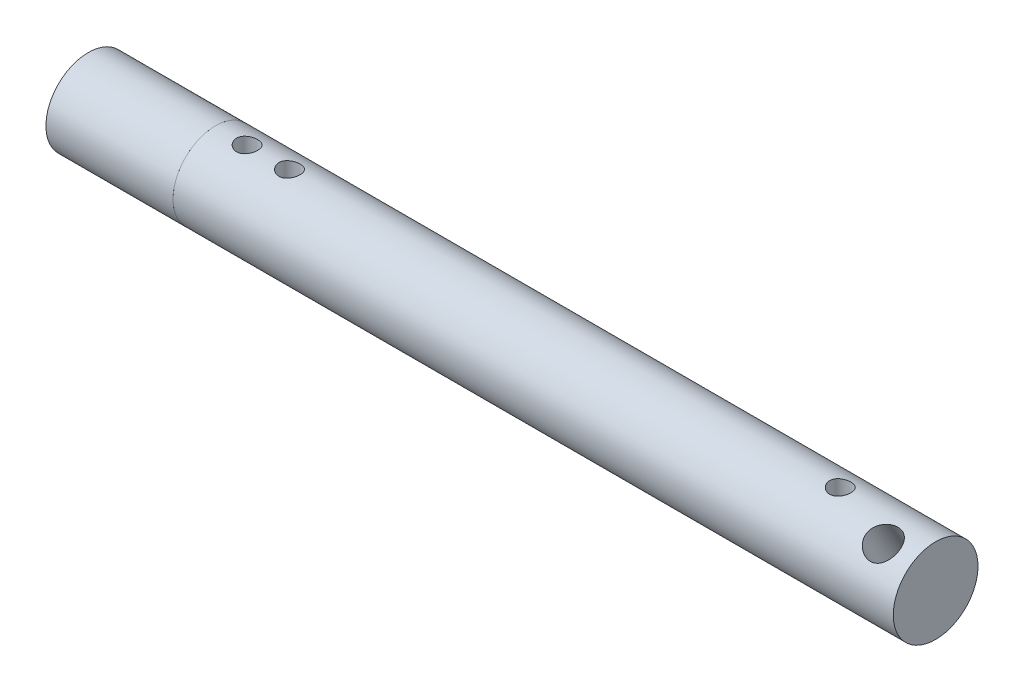
SolidWorks part; units mm, degrees
ref_plane "Front Plane" through (0, 0, 0) normal (0, 0, 1) x (1, 0, 0)
ref_plane "Top Plane" through (0, 0, 0) normal (0, 1, 0) x (1, 0, 0)
ref_plane "Right Plane" through (0, 0, 0) normal (1, 0, 0) x (0, 0, -1)
sketch "Sketch1" plane through (0, 0, 0) normal (1, 0, 0) x (0, 0, -1)
  line L0 (0, 0) -> (0, 12.7)
  line L1 (12.7, 3.403) -> (9.297, 9.297)
  line L2 (9.297, 9.297) -> (3.403, 12.7)
  line L3 (3.403, 12.7) -> (-3.403, 12.7)
  line L4 (-3.403, 12.7) -> (-9.297, 9.297)
  line L5 (-9.297, 9.297) -> (-12.7, 3.403)
  line L6 (-12.7, 3.403) -> (-12.7, -3.403)
  line L7 (-12.7, -3.403) -> (-9.297, -9.297)
  line L8 (-9.297, -9.297) -> (-3.403, -12.7)
  line L9 (-3.403, -12.7) -> (3.403, -12.7)
  line L10 (3.403, -12.7) -> (9.297, -9.297)
  line L11 (9.297, -9.297) -> (12.7, -3.403)
  line L12 (12.7, -3.403) -> (12.7, 3.403)
  line L13 (0, 0) -> (6.35, 10.9985)
  circle A0 centre (0, 0) radius 12.7
  circle A1 centre (0, 0) radius 12.7 construction
extrude "Boss-Extrude1" add sketch "Sketch1" along normal blind 215.9 contours L3 L4 L5 L6 L7 L8 L9 L10 L11 L12 L1 L2
sketch "Sketch2" plane through (0, 12.7, 0) normal (0, 1, 0) x (1, 0, 0)
  line L0 (0, 0) -> (9.525, 0)
  line L1 (0, 0) -> (22.225, 0)
  line L2 (0, 0) -> (187.325, 0)
  circle A0 centre (9.525, 0) radius 3.175
  circle A1 centre (22.225, 0) radius 3.175
  circle A2 centre (187.325, 0) radius 3.175
sketch "Sketch3" plane through (0, 10.9985, 6.35) normal (0, 0.866, 0.5) x (1, 0, 0)
  line L0 (0, 0) -> (206.375, 0)
  circle A0 centre (206.375, 0) radius 4.7625
extrude "Cut-Extrude1" cut sketch "Sketch2" against normal blind 215.9 contours L2 A1 L1 | L1 A1 L2 | L2 A0 L1 | L1 A0 L2 | A2
extrude "Cut-Extrude2" cut sketch "Sketch3" against normal blind 215.9 contours A0
sketch "Sketch4" plane through (0, 0, 0) normal (-1, 0, 0) x (0, 0, 1)
  circle A0 centre (0, 0) radius 12.7
  circle A1 centre (0, 0) radius 25.4351
extrude "Cut-Extrude6" cut sketch "Sketch4" against normal blind 222.25
sketch "Sketch5" plane through (0, 0, 0) normal (-1, 0, 0) x (0, 0, 1)
  circle A0 centre (0, 0) radius 12.7
extrude "Boss-Extrude2" add sketch "Sketch5" along normal blind 38.1 separate body
sketch "Sketch6" plane through (-38.1, 0, 0) normal (-1, 0, 0) x (0, 0, 1)
  circle A0 centre (0, 0) radius 12.7
extrude "Cut-Extrude7" cut sketch "Sketch6" against normal blind 38.1
sketch "Sketch7" plane through (0, 0, 0) normal (-1, 0, 0) x (0, 0, 1)
  circle A0 centre (0, 0) radius 12.7
extrude "Boss-Extrude3" add sketch "Sketch7" along normal blind 38.1 separate body
